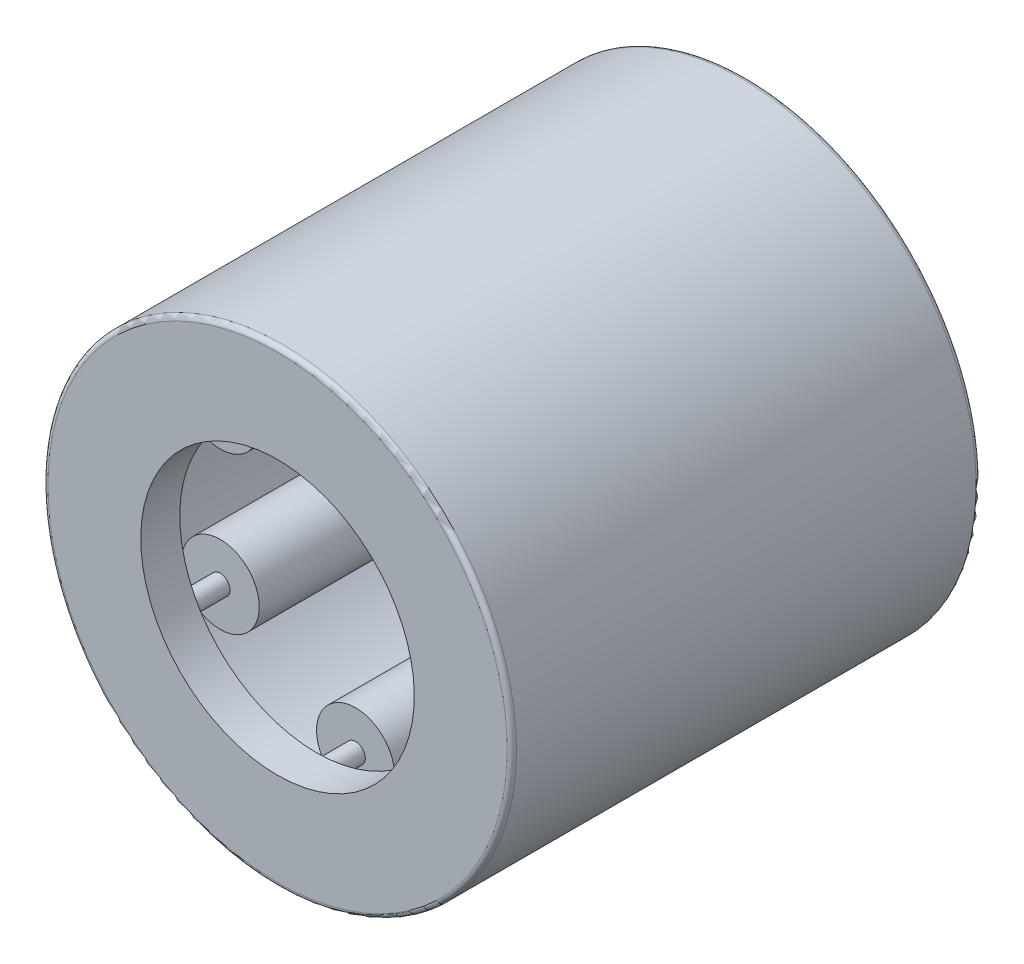
SolidWorks part; units mm, degrees
ref_plane "Front Plane" through (0, 0, 0) normal (0, 0, 1) x (1, 0, 0)
ref_plane "Top Plane" through (0, 0, 0) normal (0, 1, 0) x (1, 0, 0)
ref_plane "Right Plane" through (0, 0, 0) normal (1, 0, 0) x (0, 0, -1)
sketch "Sketch1" plane through (0, 0, 0) normal (1, 0, 0) x (0, 0, -1)
  line L0 (-4, 0) -> (4, 0) construction
  line L1 (0, 0) -> (0, 3.9965) construction
  line L2 (-4, 0) -> (-4, 3.9965) construction
  line L3 (-4, 3.9965) -> (4, 3.9965)
  line L4 (4, 3.9965) -> (4, 0) construction
  line L5 (4, 0) -> (3.3345, 0) construction
  line L6 (3.3345, 0) -> (3.3345, 3.331) construction
  line L7 (3.3345, 3.331) -> (-3.3345, 3.331)
  line L8 (-3.3345, 3.331) -> (-3.3345, 0) construction
  line L9 (-3.3345, 0) -> (-4, 0) construction
  line L10 (-4, 3.9965) -> (-4, 2.3327)
  line L11 (-4, 2.3327) -> (-3.3345, 2.3327)
  line L12 (-3.3345, 2.3327) -> (-3.3345, 3.331)
  line L13 (3.3345, 3.9965) -> (3.3345, 3.331) construction
  line L14 (3.3345, 3.331) -> (3.3345, 2.3327)
  line L15 (3.3345, 2.3327) -> (4, 2.3327)
  line L16 (4, 2.3327) -> (4, 3.9965)
  line L17 (3.3345, 3.331) -> (3.3345, 2.6655) construction
  line L18 (3.3345, 2.6655) -> (3.3345, 2) construction
  line L19 (3.3345, -3.331) -> (3.3345, -2.6655) construction
  line L20 (3.3345, -3.9965) -> (3.3345, -3.331) construction
  line L21 (4, -2.3327) -> (4, -3.9965) construction
  line L22 (3.3345, -2.3327) -> (4, -2.3327) construction
  line L23 (3.3345, -3.331) -> (3.3345, -2.3327) construction
  line L24 (-3.3345, -2.3327) -> (-3.3345, -3.331) construction
  line L25 (-4, -2.3327) -> (-3.3345, -2.3327) construction
  line L26 (-4, -3.9965) -> (-4, -2.3327) construction
  line L27 (3.3345, -3.331) -> (-3.3345, -3.331) construction
  line L28 (-4, -3.9965) -> (4, -3.9965) construction
  point P5 (0, 2)
  dimension "Width" = 8
  dimension "OD" = 7.993
  dimension "Shaft Dia" = 4
revolve "Revolve1" add sketch "Sketch1" angle 360 about L0
sketch "Sketch2" plane through (0, 0, 0) normal (1, 0, 0) x (0, 0, -1)
  line L0 (3.3345, 3.331) -> (-3.3345, 3.331) construction
  line L1 (-2.669, 2.6655) -> (2.669, 2.6655) construction
  line L2 (-2.669, 2.6655) -> (-2.669, 3.331) construction
  line L3 (-2.669, 3.331) -> (2.669, 3.331)
  line L4 (2.669, 2.6655) -> (2.669, 3.331) construction
  line L5 (3.3345, 2.3327) -> (4, 2.3327) construction
  line L6 (-3.3345, 2.6655) -> (-2.669, 2.6655) construction
  line L7 (2.669, 2.6655) -> (3.3345, 2.6655) construction
  line L8 (-4, 2.3327) -> (-3.3345, 2.3327) construction
  line L9 (-2.669, 2.8319) -> (-2.669, 2.4991) construction
  line L10 (-3.3345, 2.6655) -> (-3.3345, 2.3327) construction
  line L11 (-2.669, 3.331) -> (-2.669, 2.8319)
  line L12 (2.669, 3.331) -> (2.669, 2.8319)
  line L13 (2.669, 2.8319) -> (-2.669, 2.8319)
  line L14 (0, 3.331) -> (0, 2) construction
  line L15 (-3.3345, 2.3327) -> (-3.3345, 3.331) construction
  line L16 (-2.669, 2.4991) -> (-3.3345, 2.4991) construction
  line L17 (0, 0) -> (4, 0) construction
  line L18 (-2.669, -2.4991) -> (-3.3345, -2.4991) construction
  line L19 (0, -3.331) -> (0, -2) construction
  line L20 (-3.3345, -2.6655) -> (-3.3345, -2.3327) construction
  line L21 (-2.669, -2.8319) -> (-2.669, -2.4991) construction
  line L22 (2.669, -2.6655) -> (3.3345, -2.6655) construction
  line L23 (-3.3345, -2.6655) -> (-2.669, -2.6655) construction
  line L24 (2.669, -2.6655) -> (2.669, -3.331) construction
  line L25 (-2.669, -2.6655) -> (-2.669, -3.331) construction
  line L26 (-2.669, -2.6655) -> (2.669, -2.6655) construction
  line L27 (2.669, -2.8319) -> (-2.669, -2.8319) construction
  line L28 (2.669, -3.331) -> (2.669, -2.8319) construction
  line L29 (-2.669, -3.331) -> (-2.669, -2.8319) construction
  line L30 (-2.669, -3.331) -> (2.669, -3.331) construction
  line L31 (4, -3.9965) -> (4, 3.9965) construction
  line L32 (3.3345, 3.331) -> (3.3345, 2.3327) construction
  point P16 (0, 2.6655)
revolve "Revolve2" add sketch "Sketch2" angle 360 about L1
sketch "Sketch3" plane through (0, 0, 0) normal (1, 0, 0) x (0, 0, -1)
  line L0 (3.3345, 3.331) -> (3.3345, 2.3327) construction
  line L1 (-3.3345, 2.6655) -> (3.3345, 2.6655)
  line L2 (-3.3345, 2.6655) -> (-3.3345, 2.8319)
  line L3 (-3.3345, 2.8319) -> (3.3345, 2.8319)
  line L4 (3.3345, 2.6655) -> (3.3345, 2.8319)
  line L5 (0, 0) -> (4, 0) construction
  line L6 (4, -3.9965) -> (4, 3.9965) construction
  line L7 (3.3345, -2.6655) -> (3.3345, -2.8319) construction
  line L8 (-3.3345, -2.8319) -> (3.3345, -2.8319) construction
  line L9 (-3.3345, -2.6655) -> (-3.3345, -2.8319) construction
  line L10 (-3.3345, -2.6655) -> (3.3345, -2.6655) construction
revolve "Revolve3" add sketch "Sketch3" angle 360 about L1
ref_axis "Axis1" through (0, 0, -4) along (0, 0, 1)
pattern_circular "CirPattern1" count 6 every 60 about axis through (0, 0, -4) along (0, 0, 1) of bodies 167 166
fillet "Fillet1" radius 0.0799 2 edges at (0, -3.9965, -4) (0, -3.9965, 4)
sketch "Sketch4" plane through (0, 0, 0) normal (1, 0, 0) x (0, 0, -1)
  line L0 (2.669, 3.331) -> (2.669, 2.8319) construction
  line L1 (3.9201, 2) -> (2.669, 2)
  line L2 (3.9201, 2) -> (3.9201, 2.3327)
  line L3 (3.9201, 2.3327) -> (2.669, 2.3327)
  line L4 (2.669, 2) -> (2.669, 2.3327)
  line L5 (-4, 2.3327) -> (-3.3345, 2.3327) construction
  line L6 (3.9201, -3.9965) -> (3.9201, 3.9965) construction
revolve "Revolve4" [suppressed] add sketch "Sketch4" angle 360 about L0
sketch "Sketch5" plane through (0, 0, 0) normal (1, 0, 0) x (0, 0, -1)
  line L0 (-3.9201, 3.9965) -> (-3.9201, -3.9965) construction
  line L1 (-2.669, 2) -> (-3.9201, 2)
  line L2 (-2.669, 2) -> (-2.669, 2.3327)
  line L3 (-2.669, 2.3327) -> (-3.9201, 2.3327)
  line L4 (-3.9201, 2) -> (-3.9201, 2.3327)
  line L5 (-2.669, 3.331) -> (-2.669, 2.8319) construction
revolve "Revolve5" [suppressed] add sketch "Sketch5" angle 360 about L0
sketch "Sketch6" plane through (0, 0, 0) normal (0, 0, 1) x (1, 0, 0)
  circle A0 centre (0, 0) radius 2 construction
equation "\"Rollers@CirPattern1\" = \"OD@Sketch1\"*.75"
equation "\"D1@Fillet1\" = \"OD@Sketch1\"*.01"
equation "\"Angle@CirPattern1\"= 360 / \"Rollers@CirPattern1\""
